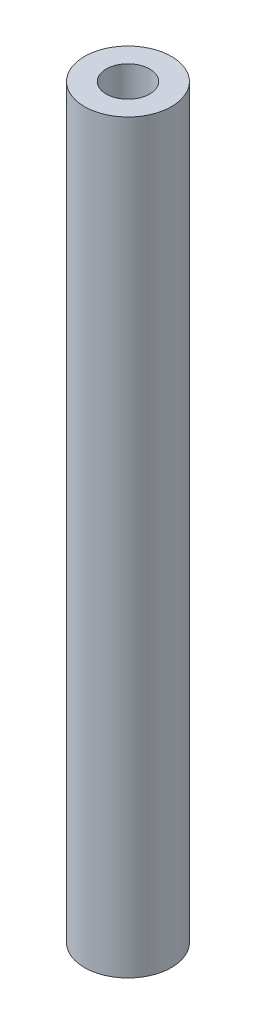
SolidWorks part; units mm, degrees
ref_plane "Front Plane" through (0, 0, 0) normal (0, 0, 1) x (1, 0, 0)
ref_plane "Top Plane" through (0, 0, 0) normal (0, 1, 0) x (1, 0, 0)
ref_plane "Right Plane" through (0, 0, 0) normal (1, 0, 0) x (0, 0, -1)
sketch "Sketch1" plane through (0, 0, 0) normal (0, 1, 0) x (1, 0, 0)
  circle A0 centre (0, 0) radius 1.75
  circle A1 centre (0, 0) radius 3.5
  dimension "D1" = 7
  dimension "D2" = 3.5
extrude "Boss-Extrude1" add sketch "Sketch1" along normal blind 60
cosmetic thread "Cosmetic Thread1" parameters "D2"=4
